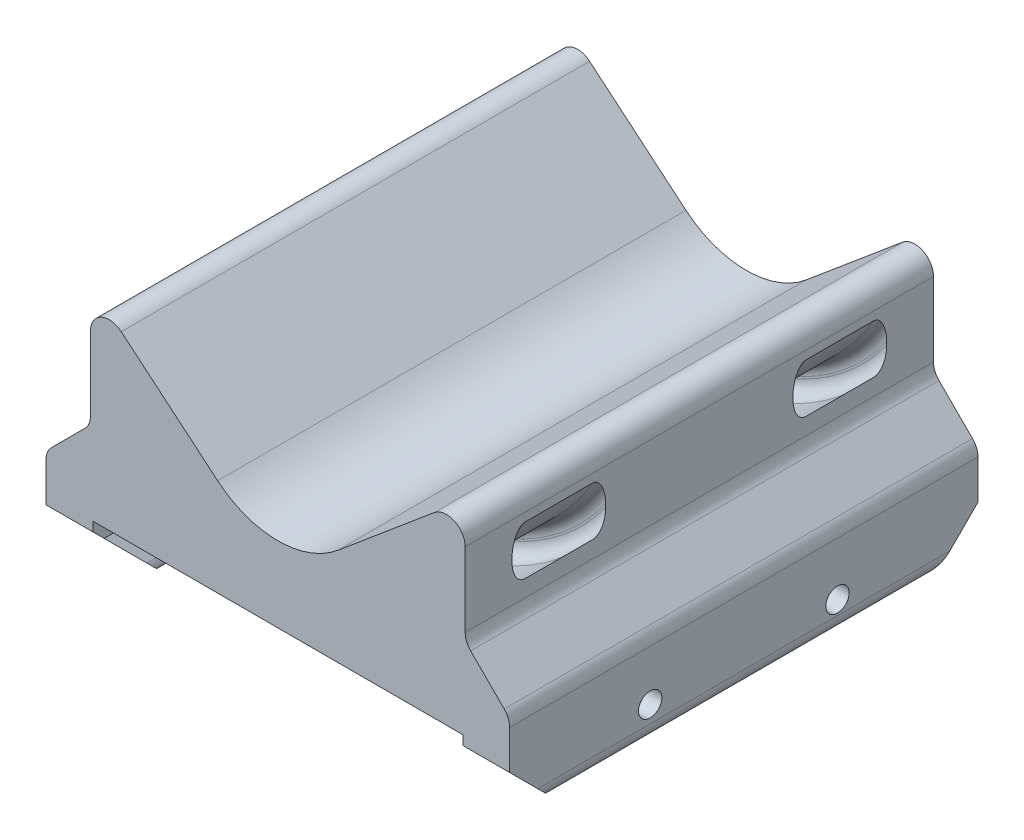
SolidWorks part; units mm, degrees
ref_plane "Front Plane" through (0, 0, 0) normal (0, 0, 1) x (1, 0, 0)
ref_plane "Top Plane" through (0, 0, 0) normal (0, 1, 0) x (1, 0, 0)
ref_plane "Right Plane" through (0, 0, 0) normal (1, 0, 0) x (0, 0, -1)
sketch "Sketch1" plane through (0, 0, 0) normal (0, 0, 1) x (1, 0, 0)
  line L0 (0, 15.6125) -> (0, -8.5333) construction
  line L1 (6.4279, 10.3936) -> (16.7144, 19.0251)
  line L2 (20, 17.493) -> (20, 9.5784)
  line L3 (20.5858, 8.1642) -> (24.1642, 4.5858)
  line L4 (24.75, 3.1716) -> (24.75, -4)
  line L5 (22.75, -6) -> (18.277, -6)
  line L7 (19.75, 0) -> (-19.75, 0)
  line L9 (-22.75, -6) -> (-18.277, -6)
  line L10 (-24.75, 3.1716) -> (-24.75, -4)
  line L11 (-20.5858, 8.1642) -> (-24.1642, 4.5858)
  line L12 (-20, 17.493) -> (-20, 9.5784)
  line L13 (-6.4279, 10.3936) -> (-16.7144, 19.0251)
  line L14 (-19.05, -0.1) -> (19.05, -0.1) construction
  line L15 (19.05, -0.1) -> (19.05, -2.1) construction
  line L16 (19.05, -2.1) -> (13.05, -8.1) construction
  line L17 (13.05, -8.1) -> (-13.05, -8.1) construction
  line L18 (-13.05, -8.1) -> (-19.05, -2.1) construction
  line L19 (-19.05, -0.1) -> (-19.05, -2.1) construction
  line L20 (17.6642, -4.6858) -> (19.75, -2.2)
  line L21 (19.75, -2.2) -> (19.75, 0)
  line L22 (-19.75, -2.2) -> (-19.75, 0)
  line L23 (-17.6642, -4.6858) -> (-19.75, -2.2)
  arc A0 (-6.4279, 10.3936) -> (6.4279, 10.3936) centre (0, 18.0541) ccw
  arc A1 (20, 9.5784) -> (20.5858, 8.1642) centre (22, 9.5784) ccw
  arc A2 (24.1642, 4.5858) -> (24.75, 3.1716) centre (22.75, 3.1716) cw
  arc A3 (24.75, -4) -> (22.75, -6) centre (22.75, -4) cw
  arc A4 (-22.75, -6) -> (-24.75, -4) centre (-22.75, -4) cw
  arc A5 (-24.75, 3.1716) -> (-24.1642, 4.5858) centre (-22.75, 3.1716) cw
  arc A6 (-20.5858, 8.1642) -> (-20, 9.5784) centre (-22, 9.5784) ccw
  arc A7 (16.7144, 19.0251) -> (20, 17.493) centre (18, 17.493) cw
  arc A8 (-20, 17.493) -> (-16.7144, 19.0251) centre (-18, 17.493) cw
  arc A9 (18.277, -6) -> (17.6642, -4.6858) centre (18.277, -5.2) cw
  arc A10 (-17.6642, -4.6858) -> (-18.277, -6) centre (-18.277, -5.2) cw
  point P11 (0, 0)
  point P19 (0, 5)
  point P22 (20, 8.75)
  point P25 (24.75, 4)
  point P28 (24.75, -6)
  point P31 (-24.75, -6)
  point P34 (-24.75, 4)
  point P37 (-20, 8.75)
  point P40 (20, 21.782)
  point P43 (-20, 21.782)
  point P51 (0, -8.1)
  point P52 (0, -0.1)
  point P56 (16.5614, -6)
  point P59 (-16.5614, -6)
  dimension "D10" = 10
  dimension "D11" = 2
  dimension "D18" = 0.8
  dimension "D1" = 19.75
  dimension "D2" = 5
  dimension "D3" = 20
  dimension "D4" = 135
  dimension "D5" = 50
  dimension "D6" = 6
  dimension "D7" = 4
  dimension "D8" = 50
  dimension "D9" = 5
  dimension "D12" = 38.1
  dimension "D13" = 135
  dimension "D14" = 8
  dimension "D15" = 2
  dimension "D16" = 0.2
  dimension "D17" = 2.2
extrude "Boss-Extrude1" add sketch "Sketch1" along normal blind 50
sketch "Sketch2" plane through (0, 0, 0) normal (1, 0, 0) x (0, 0, -1)
  line L0 (-50, 0) -> (0, 0) construction
  line L1 (-5, 5) -> (-15, 5)
  line L2 (-5, 5) -> (-5, 2)
  line L3 (-5, 2) -> (-15, 2)
  line L4 (-15, 5) -> (-15, 2)
  line L5 (0, 4.5858) -> (0, 8.1642) construction
  line L6 (-35, 5) -> (-45, 5)
  line L7 (-35, 5) -> (-35, 2)
  line L8 (-35, 2) -> (-45, 2)
  line L9 (-45, 5) -> (-45, 2)
  line L14 (-39.3538, 28.0541) -> (45.5998, 28.0541) construction
  line L15 (-50, 8.0541) -> (0, 8.0541) construction
  dimension "D1" = 10
  dimension "D2" = 3
  dimension "D3" = 2
  dimension "D4" = 5
  dimension "D6" = 20
  dimension "D5" = 2
revolve "Cut-Revolve1" cut sketch "Sketch2" angle 360 about L14
hole_wizard "M3x0.5 Tapped Hole1" positions "Sketch3" profile "Sketch4" tap size "M3x0.5" standard "ANSI Metric" end condition through all
sketch "Sketch3" plane through (-24.75, 0, 0) normal (-1, 0, 0) x (0, 0, 1)
  point P2 (15, -2.5)
  point P12 (34.9977, -2.1958)
  point P20 (0, 0)
  point P21 (0, 0)
  point P22 (0, 0)
  point P23 (11.3295, -2.524)
  point P24 (0, 0)
  point P30 (5.2993, -13.333)
  dimension "D1" = 2.5
  dimension "D2" = 15
  dimension "D3" = 20
sketch "Sketch4" plane through (-24.75, -2.5, 15) normal (0, 1, 0) x (0, 0, 1)
  line L0 (0, 0) -> (0, 49.5)
  line L1 (0, 49.5) -> (1.25, 49.5)
  line L2 (1.25, 49.5) -> (1.25, 0.275)
  line L3 (1.25, 0.275) -> (1.525, 0)
  line L5 (1.525, 0) -> (0, 0)
  line L6 (-1.25, 0.275) -> (-1.525, 0) construction
  line L11 (0, -6.35) -> (0, 107.95) construction
  dimension "Thru Tap Drill Dia." = 2.5
  dimension "Thru Tap Drill Depth" = 49.5
  dimension "Near C'Sink Dia." = 3.05
  dimension "Near C'Sink Angle" = 90
cosmetic thread "Hole Thread3" parameters "D2"=3
cosmetic thread "Hole Thread4" parameters "D2"=3
fillet "Fillet2" radius 1.4 8 edges at (0, 2, 45) (0, 2, 35) (0, 5, 45) (0, 5, 35) (0, 2, 5) (0, 2, 15) (0, 5, 5) (0, 5, 15)
sketch "Sketch5" plane through (0, 0, 0) normal (0, 0, -1) x (-1, 0, 0)
  line L0 (20.9423, 0) -> (20.9423, -6)
  line L1 (20.9423, -6) -> (-21.7222, -6)
  line L2 (-18.277, -6) -> (-22.75, -6) construction
  line L3 (-21.7222, -6) -> (-21.7222, 0)
  line L4 (-21.7222, 0) -> (20.9423, 0)
  line L5 (19.75, 0) -> (-19.75, 0) construction
  line L6 (22.75, -6) -> (18.277, -6) construction
extrude "Boss-Extrude2" add sketch "Sketch5" against normal blind 5
sketch "Sketch6" plane through (20, 0, 0) normal (1, 0, 0) x (0, 0, -1)
  line L0 (-50, 32.9238) -> (-50, -1)
  line L1 (-50, -4) -> (-50, 3.1716) construction
  line L2 (-50, -1) -> (-45, -6)
  line L3 (-50, -6) -> (0, -6) construction
  line L4 (-45, -6) -> (-5, -6)
  line L5 (-5, -6) -> (0, -1)
  line L6 (0, -1) -> (0, 27.6375)
  line L7 (0, 27.6375) -> (9.7157, 27.6375)
  line L8 (9.7157, 27.6375) -> (9.7157, -14.5127)
  line L9 (9.7157, -14.5127) -> (-61.0493, -14.5127)
  line L10 (-61.0493, -14.5127) -> (-61.0493, 32.9238)
  line L11 (-61.0493, 32.9238) -> (-50, 32.9238)
  line L12 (-50, -4) -> (-50, -6) construction
  line L13 (0, -6) -> (0, -4) construction
  dimension "D1" = 225
  dimension "D2" = 225
  dimension "D3" = 5
  dimension "D4" = 5
extrude "Cut-Extrude1" cut sketch "Sketch6" against normal through all both and the other way through all
